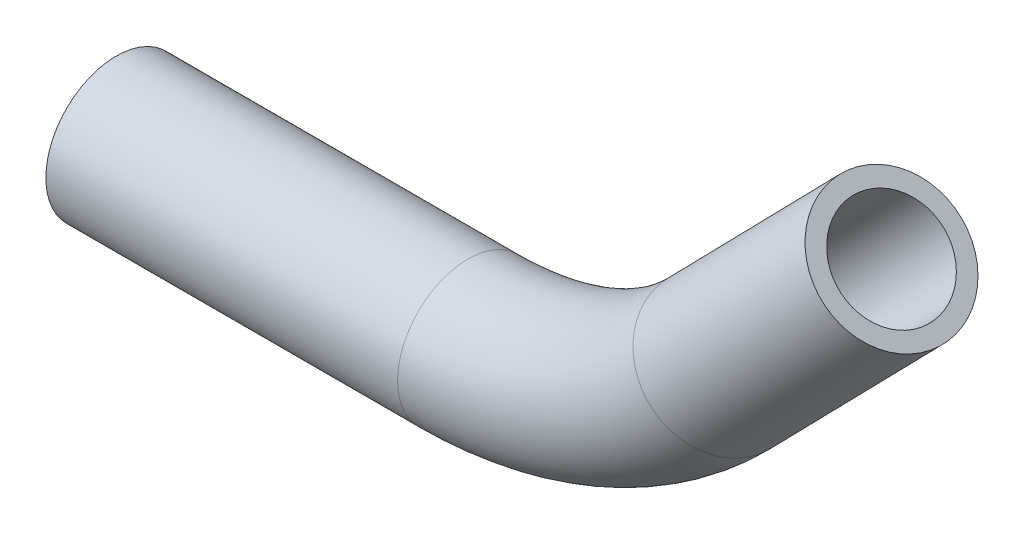
SolidWorks part; units mm, degrees
material "Сталь 3 ГОСТ 535-88"
ref_plane "Спереди" through (0, 0, 0) normal (0, 0, 1) x (1, 0, 0)
ref_plane "Сверху" through (0, 0, 0) normal (0, 1, 0) x (1, 0, 0)
ref_plane "Справа" through (0, 0, 0) normal (1, 0, 0) x (0, 0, -1)
sketch "Эскиз1" plane through (0, 0, 0) normal (0, 0, 1) x (1, 0, 0)
  line L0 (0, 0) -> (20, 0)
  line L1 (34.3074, 6.025) -> (44.0898, 16.0402)
  arc A0 (20, 0) -> (34.3074, 6.025) centre (20, 20) ccw
  point P5 (44.0898, 16.0402)
  dimension "D1" = 20
  dimension "D2" = 20
  dimension "D3" = 14
sketch "Эскиз2" plane through (0, 0, 0) normal (1, 0, 0) x (0, 0, -1)
  circle A0 centre (0, 0) radius 4
  circle A1 centre (0, 0) radius 3
  dimension "D1" = 8
  dimension "D2" = 1
sweep "По траектории1" add profiles "Эскиз2" path "Эскиз1"
